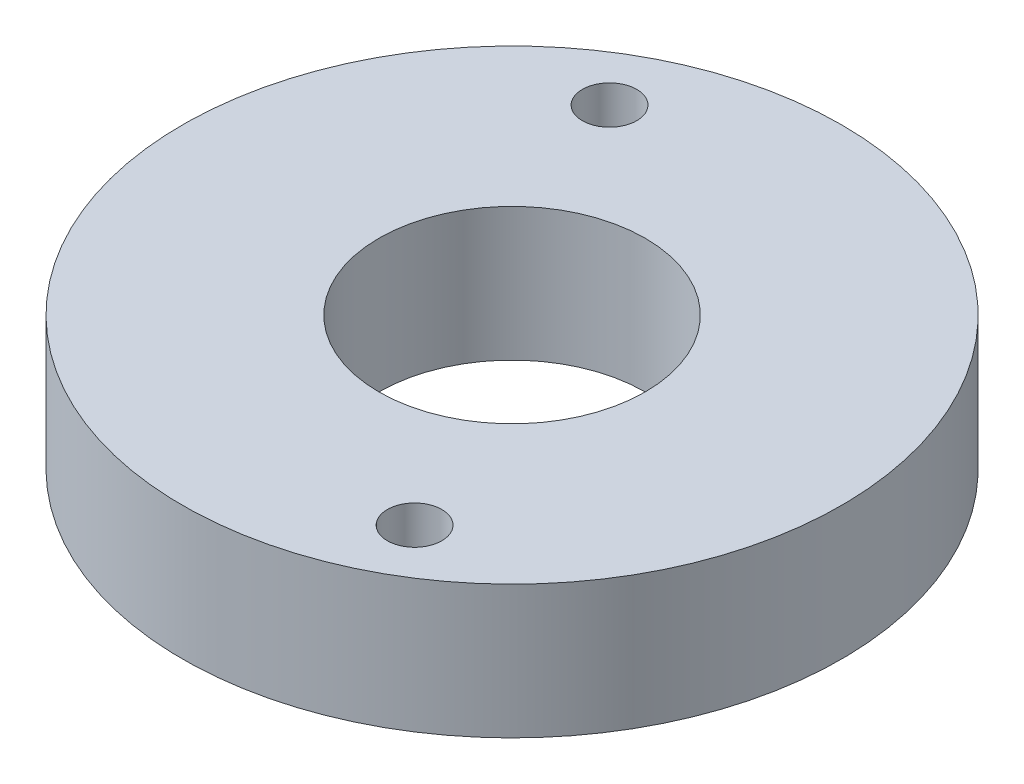
SolidWorks part; units mm, degrees
ref_plane "Front Plane" through (0, 0, 0) normal (0, 0, 1) x (1, 0, 0)
ref_plane "Top Plane" through (0, 0, 0) normal (0, 1, 0) x (1, 0, 0)
ref_plane "Right Plane" through (0, 0, 0) normal (1, 0, 0) x (0, 0, -1)
sketch "Sketch1" plane through (0, 0, 0) normal (0, 0, 1) x (1, 0, 0)
  line L2 (37.719, 0) -> (37.719, 15.24)
  line L3 (37.719, 15.24) -> (15.24, 15.24)
  line L4 (15.24, 15.24) -> (15.24, 0)
  line L5 (0, 0) -> (0, 12.9368) construction
  spline S0 degree 2 poles (15.24, 0) (26.4689, 6.7973) (37.719, 0) knots 0 0 0 1 1 1
  dimension "D1" = 15.24
  dimension "D2" = 37.719
  dimension "D3" = 15.24
  dimension "D4" = 22.479
revolve "Revolve1" add sketch "Sketch1" angle 360 about L5
sketch "Sketch2" plane through (0, 15.24, 0) normal (0, 1, 0) x (1, 0, 0)
  line L0 (0, 0) -> (15.24, -26.3965) construction
  line L2 (0, 0) -> (-15.24, 26.3965) construction
  circle A1 centre (15.24, -26.3965) radius 3.1115
  circle A2 centre (-15.24, 26.3965) radius 3.1115
  circle A3 centre (0, 0) radius 30.48
  dimension "D2" = 180
  dimension "D7" = 6.223
  dimension "D3" = 60.96
  dimension "D1" = 6.223
extrude "Cut-Extrude1" cut sketch "Sketch2" against normal blind 7.62 contours A1 A3 | A3 A1 | A3 A2
sketch "Sketch3" plane through (0, 0, 0) normal (0, 0, 1) x (1, 0, 0)
  line L0 (15.24, 0) -> (22.86, 0)
  line L1 (15.24, 0) -> (15.24, 8.89)
  line L2 (15.24, 8.89) -> (22.86, 0)
  line L3 (0, 0) -> (0, 26.4553) construction
